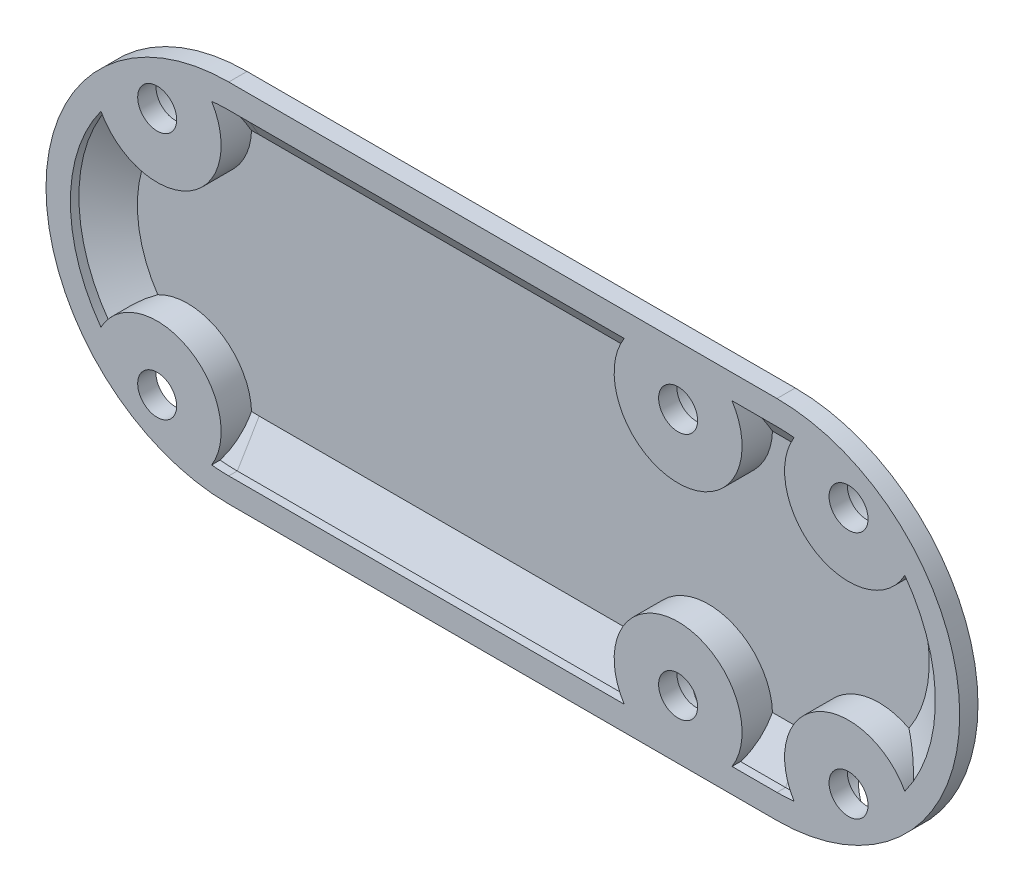
SolidWorks part; units mm, degrees
ref_plane "Front" through (0, 0, 0) normal (0, 0, 1) x (1, 0, 0)
ref_plane "Top" through (0, 0, 0) normal (0, 1, 0) x (1, 0, 0)
ref_plane "Right" through (0, 0, 0) normal (1, 0, 0) x (0, 0, -1)
sketch "Sketch1" plane through (0, 0, 0) normal (0, 0, 1) x (1, 0, 0)
  line L0 (-36.885, 0) -> (8.115, 0) construction
  line L1 (-36.885, 15) -> (8.115, 15)
  line L2 (-36.885, -15) -> (8.115, -15)
  line L3 (13.99, 10.175) -> (13.99, -12.64) construction
  line L4 (-14.385, 6.1701) -> (-14.385, 0) construction
  line L5 (0, 10.175) -> (0, 0) construction
  line L6 (-42.76, 10.175) -> (-42.76, -7.5125) construction
  line L7 (-36.885, 0) -> (-46.5551, 0) construction
  arc A0 (-36.885, 15) -> (-36.885, -15) centre (-36.885, 0) ccw
  arc A1 (8.115, -15) -> (8.115, 15) centre (8.115, 0) ccw
  circle A2 centre (-42.76, 10.175) radius 1.5 construction
  circle A3 centre (13.99, 10.175) radius 1.5 construction
  circle A4 centre (0, 10.175) radius 1.5 construction
  circle A5 centre (13.99, -10.175) radius 1.5 construction
  circle A6 centre (0, -10.175) radius 1.5 construction
  circle A7 centre (-42.76, -10.175) radius 1.5 construction
  point P3 (-14.385, 0)
  dimension "D1" = 3
  dimension "D3" = 15
  dimension "D5" = 56.75
  dimension "D6" = 20.35
  dimension "D2" = 13.99
  dimension "D4" = 45
extrude "Boss-Extrude1" add sketch "Sketch1" along normal blind 4.5
sketch "Sketch2" plane through (0, 0, 4.5) normal (0, 0, 1) x (1, 0, 0)
  line L0 (-36.885, 0) -> (8.115, 0) construction
  line L1 (-36.885, 13) -> (8.115, 13)
  line L2 (-36.885, -13) -> (8.115, -13)
  arc A0 (-36.885, 13) -> (-36.885, -13) centre (-36.885, 0) ccw
  arc A1 (8.115, -13) -> (8.115, 13) centre (8.115, 0) ccw
  arc A2 (8.115, -15) -> (8.115, 15) centre (8.115, 0) ccw construction
  point P4 (-14.385, 0)
  dimension "D1" = 2
extrude "Cut-Extrude1" cut sketch "Sketch2" against normal blind 2.5
chamfer "Chamfer1" distance 1.8 distance2 3 4 edges at (-14.385, -13, 2) (21.115, 0, 2) (-49.885, 0, 2) (-14.385, 13, 2)
chamfer "Chamfer2" distance 4.5 distance2 3 4 edges at (-14.385, 15, 0) (-51.885, 0, 0) (23.115, 0, 0) (-14.385, -15, 0)
sketch "Sketch4" plane through (0, 0, 4.5) normal (0, 0, 1) x (1, 0, 0)
  line L0 (-36.885, 13) -> (8.115, 13) construction
  line L1 (-4.4251, 13) -> (4.4251, 13)
  line L2 (-36.885, -13) -> (8.115, -13) construction
  line L3 (-4.4251, -13) -> (4.4251, -13)
  arc A0 (-47.377, 7.6758) -> (-38.2873, 12.9241) centre (-42.76, 10.175) ccw
  arc A1 (-4.4251, 13) -> (4.4251, 13) centre (0, 10.175) ccw
  arc A2 (9.5173, 12.9241) -> (18.607, 7.6758) centre (13.99, 10.175) ccw
  arc A3 (18.607, -7.6758) -> (9.5173, -12.9241) centre (13.99, -10.175) ccw
  arc A4 (4.4251, -13) -> (-4.4251, -13) centre (0, -10.175) ccw
  arc A5 (-38.2873, -12.9241) -> (-47.377, -7.6758) centre (-42.76, -10.175) ccw
  arc A6 (-36.885, 13) -> (-36.885, -13) centre (-36.885, 0) ccw construction
  arc A7 (-38.2873, 12.9241) -> (-47.377, 7.6758) centre (-36.885, 0) ccw
  arc A8 (8.115, -13) -> (8.115, 13) centre (8.115, 0) ccw construction
  arc A9 (9.5173, -12.9241) -> (18.607, -7.6758) centre (8.115, 0) ccw
  arc A10 (-47.377, -7.6758) -> (-38.2873, -12.9241) centre (-36.885, 0) ccw
  arc A11 (18.607, 7.6758) -> (9.5173, 12.9241) centre (8.115, 0) ccw
  dimension "D1" = 10.5
extrude "Boss-Extrude2" add sketch "Sketch4" against normal up to body
sketch "Sketch3" plane through (0, 0, 0) normal (0, 0, -1) x (-1, 0, 0)
  circle A0 centre (-13.99, 10.175) radius 2.975
  circle A1 centre (0, 10.175) radius 2.975
  circle A2 centre (42.76, 10.175) radius 2.975
  circle A3 centre (42.76, -10.175) radius 2.975
  circle A4 centre (0, -10.175) radius 2.975
  circle A5 centre (-13.99, -10.175) radius 2.975
  dimension "D1" = 5.95
extrude "Cut-Extrude2" cut sketch "Sketch3" against normal blind 3
sketch "Sketch5" plane through (0, 0, 3) normal (0, 0, -1) x (-1, 0, 0)
  circle A0 centre (-13.99, 10.175) radius 1.6
  circle A1 centre (0, 10.175) radius 1.6
  circle A2 centre (42.76, 10.175) radius 1.6
  circle A3 centre (42.76, -10.175) radius 1.6
  circle A4 centre (0, -10.175) radius 1.6
  circle A5 centre (-13.99, -10.175) radius 1.6
  dimension "D1" = 3.2
extrude "Cut-Extrude3" cut sketch "Sketch5" against normal up to next
